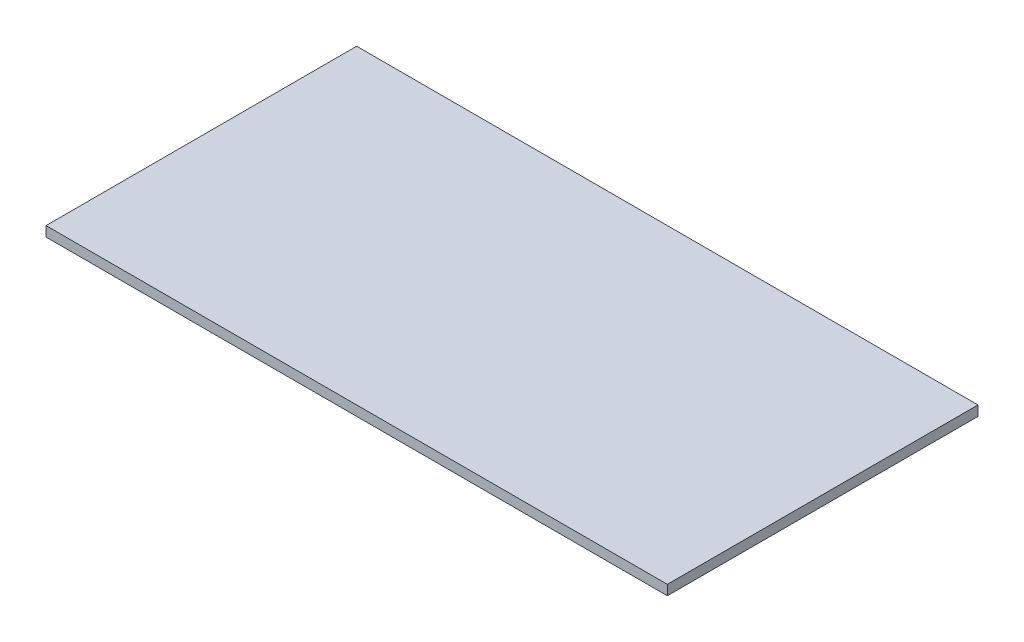
SolidWorks part; units mm, degrees
material "Плата обработки данных, сложная"
ref_plane "Спереди" through (0, 0, 0) normal (0, 0, 1) x (1, 0, 0)
ref_plane "Сверху" through (0, 0, 0) normal (0, 1, 0) x (1, 0, 0)
ref_plane "Справа" through (0, 0, 0) normal (1, 0, 0) x (0, 0, -1)
sketch "Эскиз1" plane through (0, 0, 0) normal (0, 1, 0) x (1, 0, 0)
  line L1 (-50, 25) -> (50, 25)
  line L2 (-50, 25) -> (-50, -25)
  line L3 (-50, -25) -> (50, -25)
  line L4 (50, 25) -> (50, -25)
  line L5 (-50, 25) -> (50, -25) construction
  line L6 (-50, -25) -> (50, 25) construction
  point P0 (0, 0)
  dimension "D1" = 50
  dimension "D2" = 100
extrude "Бобышка-Вытянуть1" add sketch "Эскиз1" along normal blind 1.6
